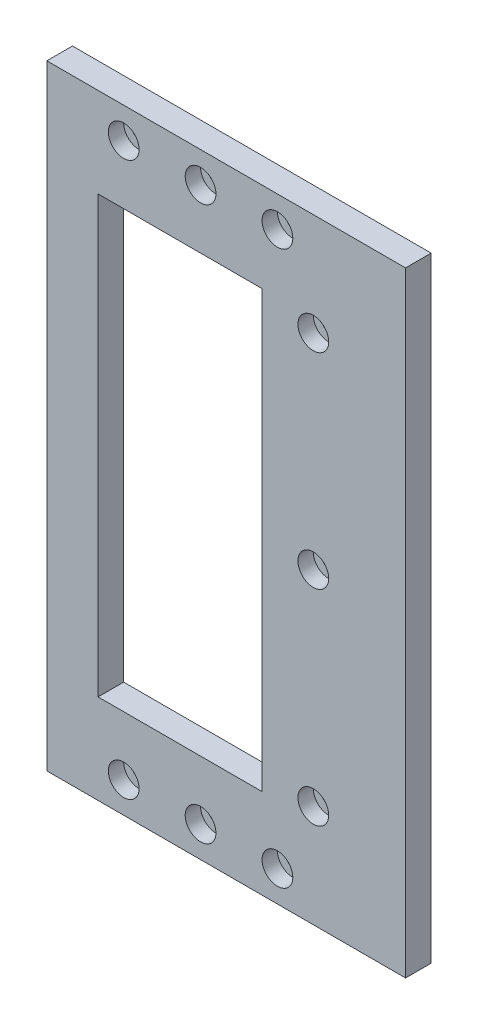
SolidWorks part; units mm, degrees
ref_plane "前基準面" through (0, 0, 0) normal (0, 0, 1) x (1, 0, 0)
ref_plane "上基準面" through (0, 0, 0) normal (0, 1, 0) x (1, 0, 0)
ref_plane "右基準面" through (0, 0, 0) normal (1, 0, 0) x (0, 0, -1)
sketch "草圖3" plane through (0, 0, 0) normal (0, 0, 1) x (1, 0, 0)
  line L0 (0, 0) -> (0, -60) construction
  line L5 (-30, 60) -> (-30, -60)
  line L6 (40, 60) -> (40, -60)
  line L13 (0, -60) -> (-30, -60)
  line L26 (0, -60) -> (40, -60)
  line L27 (0, 60) -> (-30, 60)
  line L28 (0, 60) -> (40, 60)
  point P0 (0, 0)
  point P19 (0, 0)
  dimension "D1" = 60
  dimension "D5" = 30
  dimension "D6" = 40
  dimension "D8" = 120
extrude "填料-伸長1" add sketch "草圖3" along normal blind 5 contours L28 L6 L26 L13 L5 L27
hole_wizard "鑽孔2" positions "3D草圖3" profile "草圖7" legacy
sketch3d "3D草圖3"
  line L0 (0, 0, 5) -> (0, 54, 5) construction
  line L1 (0, 54, 5) -> (-15, 54, 5) construction
  line L3 (0, 54, 5) -> (15, 54, 5) construction
  line L5 (0, 0, 5) -> (0, -54, 5) construction
  line L6 (0, -54, 5) -> (-15, -54, 5) construction
  line L8 (0, -54, 5) -> (15, -54, 5) construction
  line L10 (0, 0, 5) -> (22, 0, 5) construction
  line L11 (22, 0, 5) -> (22, 40, 5) construction
  line L12 (22, 0, 5) -> (22, -40, 5) construction
  point P0 (-15, 54, 5)
  point P2 (0, 54, 5)
  point P4 (15, 54, 5)
  point P6 (22, 40, 5)
  point P8 (22, -40, 5)
  point P10 (15, -54, 5)
  point P12 (0, -54, 5)
  point P14 (-15, -54, 5)
  point P52 (22, 0, 5)
  dimension "D1" = 54
  dimension "D2" = 22
  dimension "D3" = 15
  dimension "D4" = 40
sketch "草圖7" plane through (-15, 54, 5) normal (1, 0, 0) x (0, -1, 0)
  line L0 (0, 0) -> (0, 10)
  line L1 (0, 10) -> (1.3, 10)
  line L2 (1.3, 10) -> (1.3, 3)
  line L3 (1.3, 3) -> (3, 3)
  line L4 (3, 3) -> (3, 0)
  line L5 (3, 0) -> (0, 0)
  line L6 (0, 110) -> (0, -10) construction
  dimension "直徑" = 2.6
  dimension "深度" = 10
  dimension "柱孔直徑1" = 6
  dimension "柱孔深度1" = 3
ref_plane "平面2" through (0, 0, 5) normal (0, 0, 1) x (1, 0, 0)
sketch "草圖8" plane through (0, 0, 5) normal (0, 0, 1) x (1, 0, 0)
  line L0 (0, 0) -> (-4, 0) construction
  line L2 (-20, -42.5) -> (12, -42.5)
  line L3 (-20, -42.5) -> (-20, 42.5)
  line L4 (-20, 42.5) -> (12, 42.5)
  line L5 (12, -42.5) -> (12, 42.5)
  line L6 (-20, -42.5) -> (12, 42.5) construction
  line L7 (-20, 42.5) -> (12, -42.5) construction
  dimension "D1" = 4
  dimension "D2" = 32
  dimension "D3" = 85
extrude "除料-伸長1" cut sketch "草圖8" against normal through all
